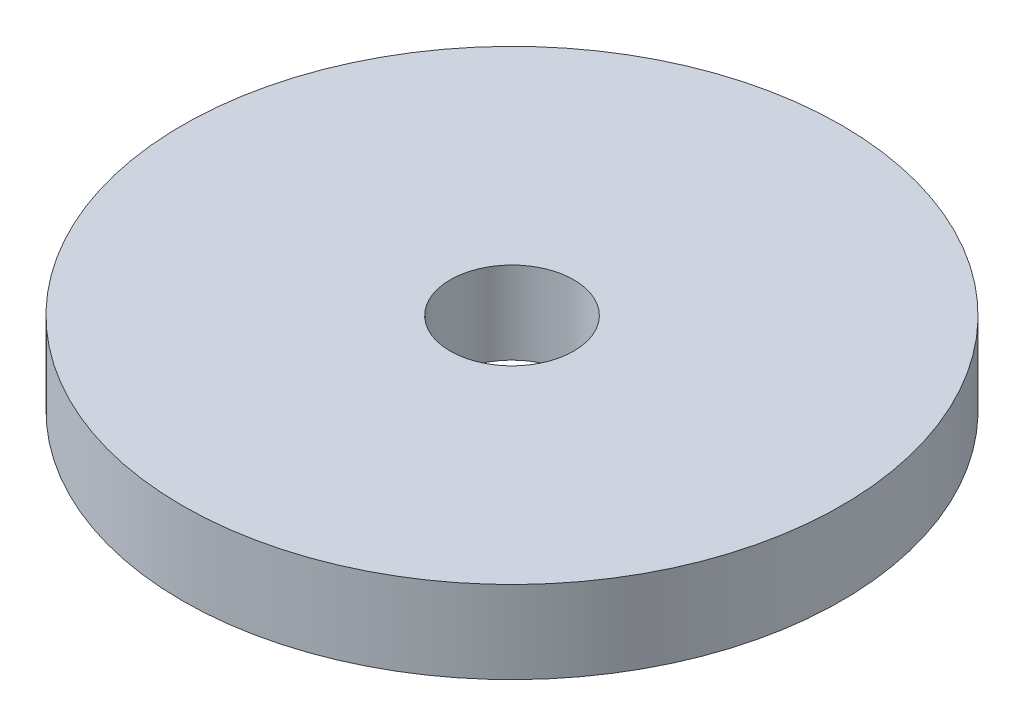
SolidWorks part; units mm, degrees
material "Galvanized Steel"
ref_plane "Front Plane" through (0, 0, 0) normal (0, 0, 1) x (1, 0, 0)
ref_plane "Top Plane" through (0, 0, 0) normal (0, 1, 0) x (1, 0, 0)
ref_plane "Right Plane" through (0, 0, 0) normal (1, 0, 0) x (0, 0, -1)
sketch "Sketch1" plane through (0, 0, 0) normal (0, 1, 0) x (1, 0, 0)
  circle A0 centre (0, 0) radius 50.8
  circle A1 centre (0, 0) radius 9.525
  dimension "D1" = 101.6
  dimension "D2" = 19.05
extrude "Boss-Extrude1" add sketch "Sketch1" along normal blind 12.7
